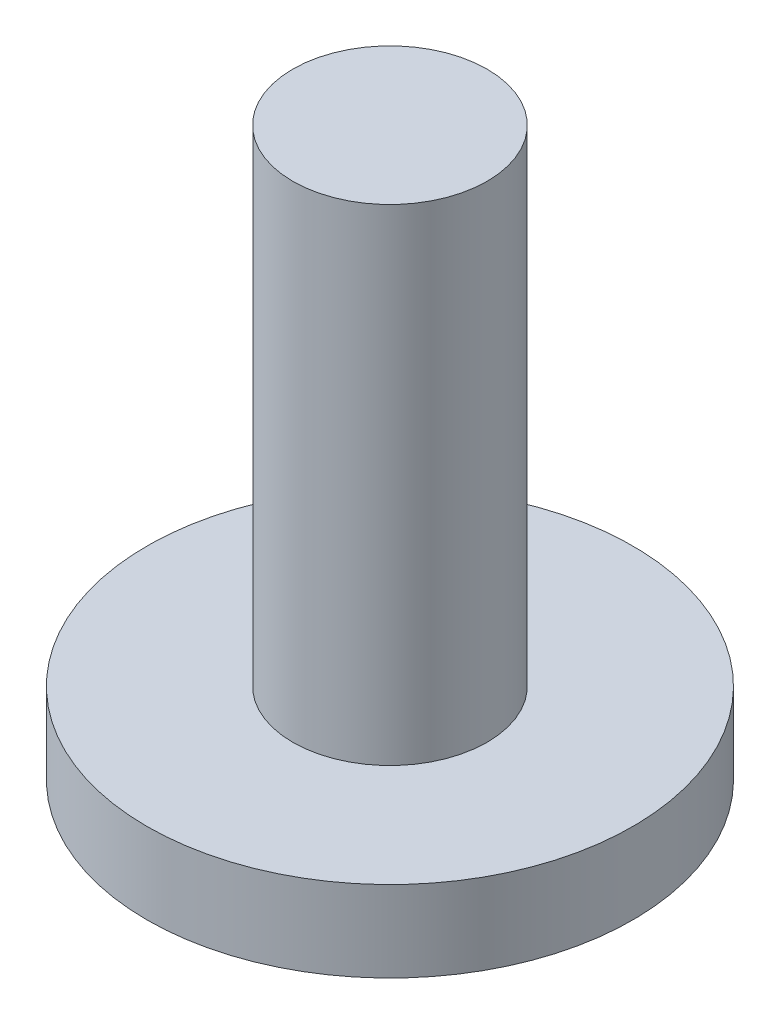
SolidWorks part; units mm, degrees
ref_plane "Front Plane" through (0, 0, 0) normal (0, 0, 1) x (1, 0, 0)
ref_plane "Top Plane" through (0, 0, 0) normal (0, 1, 0) x (1, 0, 0)
ref_plane "Right Plane" through (0, 0, 0) normal (1, 0, 0) x (0, 0, -1)
sketch "Sketch1" plane through (0, 0, 0) normal (0, 1, 0) x (1, 0, 0)
  circle A0 centre (0, 0) radius 3
  dimension "D1" = 6
extrude "Boss-Extrude1" add sketch "Sketch1" along normal blind 1
sketch "Sketch2" plane through (0, 1, 0) normal (0, 1, 0) x (1, 0, 0)
  circle A0 centre (0, 0) radius 1.2
  dimension "D1" = 2.4
extrude "Boss-Extrude2" add sketch "Sketch2" along normal blind 6
